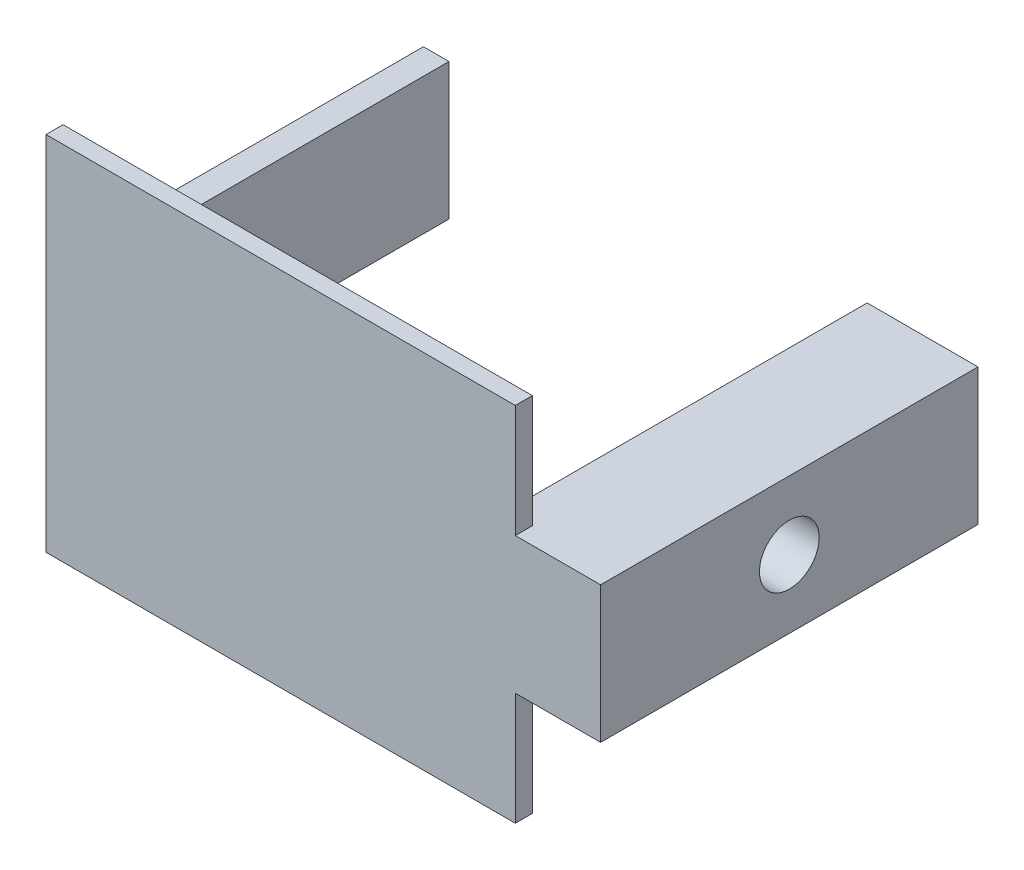
SolidWorks part; units mm, degrees
ref_plane "Front" through (0, 0, 0) normal (0, 0, 1) x (1, 0, 0)
ref_plane "Top" through (0, 0, 0) normal (0, 1, 0) x (1, 0, 0)
ref_plane "Right" through (0, 0, 0) normal (1, 0, 0) x (0, 0, -1)
sketch "Sketch1" plane through (0, 0, 0) normal (0, 0, 1) x (1, 0, 0)
  line L0 (-27.5121, 0) -> (24.5121, 0) construction
  line L1 (24.5121, 8) -> (27.5121, 8)
  line L2 (24.5121, 8) -> (24.5121, -8)
  line L3 (24.5121, -8) -> (27.5121, -8)
  line L4 (27.5121, 8) -> (27.5121, -8)
  line L5 (-24.5121, 8) -> (-27.5121, 8)
  line L6 (-24.5121, 8) -> (-24.5121, -8)
  line L7 (-24.5121, -8) -> (-27.5121, -8)
  line L8 (-27.5121, 8) -> (-27.5121, -8)
  line L10 (-24.3621, 8.3621) -> (-24.3621, -8.3621) construction
  line L11 (24.3621, -8.3621) -> (24.3621, 8.3621) construction
  dimension "D1" = 3
  dimension "D2" = 16.7243
  dimension "D3" = 16
  dimension "D4" = 0.15
  dimension "D5" = 0.15
extrude "Boss-Extrude1" add sketch "Sketch1" along normal offset from surface (42.25 mm away) 0.25
sketch "Sketch2" plane through (0, 0, 42.25) normal (0, 0, 1) x (1, 0, 0)
  line L0 (27.5121, -8) -> (27.5121, 8) construction
  line L1 (-27.5121, 21.2121) -> (27.5121, 21.2121)
  line L2 (-27.5121, 21.2121) -> (-27.5121, -21.2121)
  line L3 (-27.5121, -21.2121) -> (27.5121, -21.2121)
  line L4 (27.5121, 21.2121) -> (27.5121, -21.2121)
  line L5 (-27.5121, 8) -> (-27.5121, -8) construction
  line L8 (-51, 21.3621) -> (51, 21.3621) construction
  line L9 (-34.3621, -21.3621) -> (34.3621, -21.3621) construction
  dimension "D1" = 0.15
  dimension "D2" = 0.15
extrude "Boss-Extrude2" add sketch "Sketch2" along normal blind 2
sketch "Sketch4" plane through (27.5121, 0, 0) normal (1, 0, 0) x (0, 0, -1)
  line L0 (0, -8) -> (0, 8) construction
  line L1 (0, -8) -> (-44.25, -8)
  line L2 (0, -8) -> (0, 8)
  line L3 (0, 8) -> (-44.25, 8)
  line L4 (-44.25, -8) -> (-44.25, 8)
  line L5 (-42.25, 8) -> (0, 8) construction
  line L6 (-44.25, 0) -> (0, 0) construction
  line L7 (-44.25, -21.2121) -> (-44.25, 21.2121) construction
  circle A0 centre (-22.125, 0) radius 3.5
  dimension "D1" = 7
extrude "Boss-Extrude4" add sketch "Sketch4" along normal blind 10
